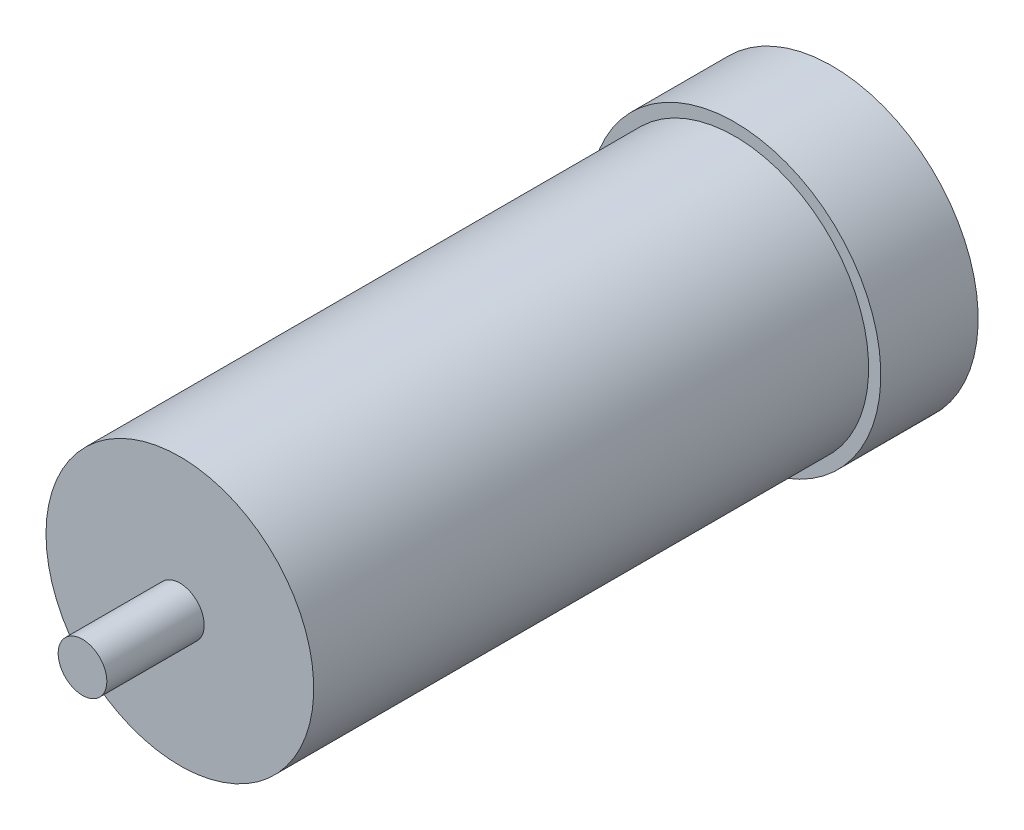
SolidWorks part; units mm, degrees
ref_plane "Front Plane" through (0, 0, 0) normal (0, 0, 1) x (1, 0, 0)
ref_plane "Top Plane" through (0, 0, 0) normal (0, 1, 0) x (1, 0, 0)
ref_plane "Right Plane" through (0, 0, 0) normal (1, 0, 0) x (0, 0, -1)
sketch "Sketch1" plane through (0, 0, 0) normal (0, 0, 1) x (1, 0, 0)
  circle A0 centre (0, 0) radius 6.875
  dimension "D1" = 13.75
extrude "Boss-Extrude1" add sketch "Sketch1" along normal blind 28.5
sketch "Sketch2" plane through (0, 0, 0) normal (0, 0, -1) x (-1, 0, 0)
  circle A0 centre (0, 0) radius 7.5
  dimension "D1" = 15
extrude "Boss-Extrude2" add sketch "Sketch2" along normal blind 5
sketch "Sketch3" plane through (0, 0, 28.5) normal (0, 0, 1) x (1, 0, 0)
  circle A0 centre (0, 0) radius 1.25
  dimension "D1" = 2.5
extrude "Boss-Extrude3" add sketch "Sketch3" along normal blind 5
